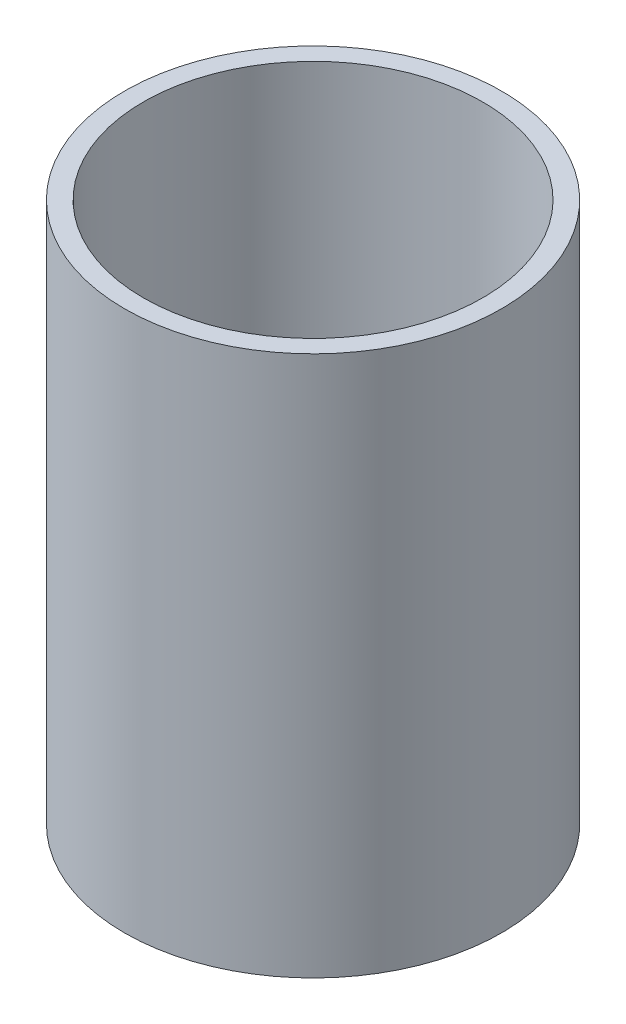
SolidWorks part; units mm, degrees
ref_plane "前视基准面" through (0, 0, 0) normal (0, 0, 1) x (1, 0, 0)
ref_plane "上视基准面" through (0, 0, 0) normal (0, 1, 0) x (1, 0, 0)
ref_plane "右视基准面" through (0, 0, 0) normal (1, 0, 0) x (0, 0, -1)
sketch "草图1" plane through (0, 0, 0) normal (0, 1, 0) x (1, 0, 0)
  circle A0 centre (0, 0) radius 15
  circle A1 centre (0, 0) radius 13.5
  dimension "D1" = 27
  dimension "D2" = 30
extrude "凸台-拉伸1" add sketch "草图1" along normal blind 43
